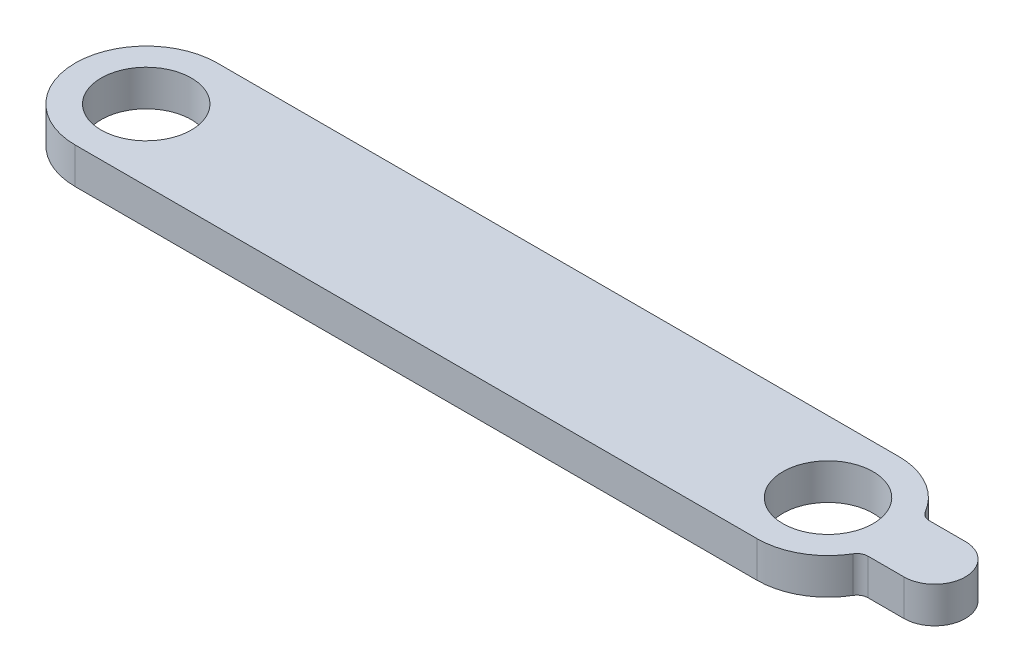
SolidWorks part; units mm, degrees
ref_plane "Front Plane" through (0, 0, 0) normal (0, 0, 1) x (1, 0, 0)
ref_plane "Top Plane" through (0, 0, 0) normal (0, 1, 0) x (1, 0, 0)
ref_plane "Right Plane" through (0, 0, 0) normal (1, 0, 0) x (0, 0, -1)
sketch "Sketch1" plane through (0, 0, 0) normal (0, 1, 0) x (1, 0, 0)
  line L0 (-30.066, 0.0378) -> (29.934, 0.0378) construction
  line L1 (-30.066, 6.2878) -> (29.934, 6.2878)
  line L2 (-30.066, -6.2122) -> (29.934, -6.2122)
  line L4 (36.1688, 2.7378) -> (39.3233, 2.7378)
  line L6 (36.1688, -2.6622) -> (39.3233, -2.6622)
  arc A0 (-30.066, 6.2878) -> (-30.066, -6.2122) centre (-30.066, 0.0378) ccw
  arc A1 (29.934, -6.2122) -> (35.3088, -3.1519) centre (29.934, 0.0378) ccw
  circle A2 centre (-30.066, 0.0378) radius 3.9688
  circle A3 centre (29.934, 0.0378) radius 3.9687
  arc A4 (35.3088, 3.2275) -> (29.934, 6.2878) centre (29.934, 0.0378) ccw
  arc A5 (39.3233, -2.6622) -> (39.3233, 2.7378) centre (39.3233, 0.0378) ccw
  arc A6 (35.3088, -3.1519) -> (36.1688, -2.6622) centre (36.1688, -3.6622) cw
  arc A7 (36.1688, 2.7378) -> (35.3088, 3.2275) centre (36.1688, 3.7378) cw
  point P2 (0, 0)
  point P16 (0, 0)
  point P19 (35.5707, -2.6622)
  point P22 (35.5707, 2.7378)
  dimension "D3" = 7.9375
  dimension "D4" = 1
  dimension "D6" = 6.25
  dimension "D7" = 6.25
  dimension "D1" = 12.5
  dimension "D2" = 60
  dimension "D5" = 5.4
extrude "Boss-Extrude1" add sketch "Sketch1" along normal blind 3.175
